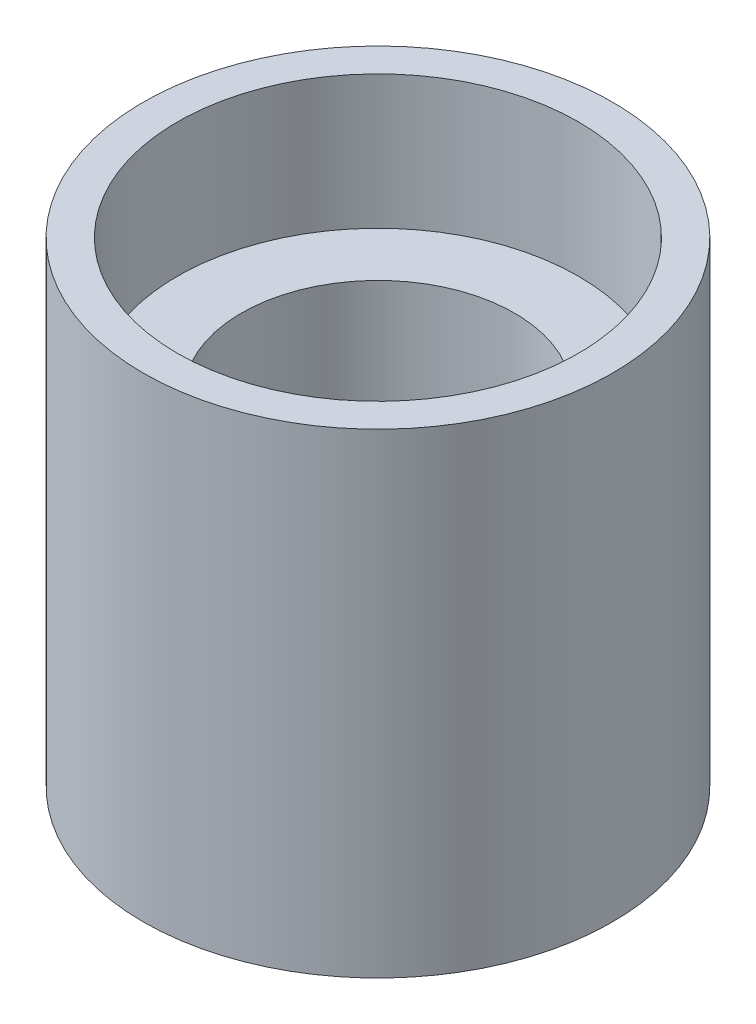
SolidWorks part; units mm, degrees
ref_plane "Front Plane" through (0, 0, 0) normal (0, 0, 1) x (1, 0, 0)
ref_plane "Top Plane" through (0, 0, 0) normal (0, 1, 0) x (1, 0, 0)
ref_plane "Right Plane" through (0, 0, 0) normal (1, 0, 0) x (0, 0, -1)
sketch "Sketch1" plane through (0, 0, 0) normal (0, 1, 0) x (1, 0, 0)
  circle A0 centre (0, 0) radius 7.9
  circle A1 centre (0, 0) radius 4.6
  dimension "D1" = 9.2
  dimension "D2" = 15.8
extrude "Boss-Extrude1" add sketch "Sketch1" along normal blind 16
ref_plane "Plane1" through (0, 16, 0) normal (0, 1, 0) x (1, 0, 0)
sketch "Sketch2" plane through (0, 16, 0) normal (0, 1, 0) x (1, 0, 0)
  circle A0 centre (0, 0) radius 6.75
  dimension "D1" = 13.5
extrude "Cut-Extrude1" cut sketch "Sketch2" against normal blind 4.5
